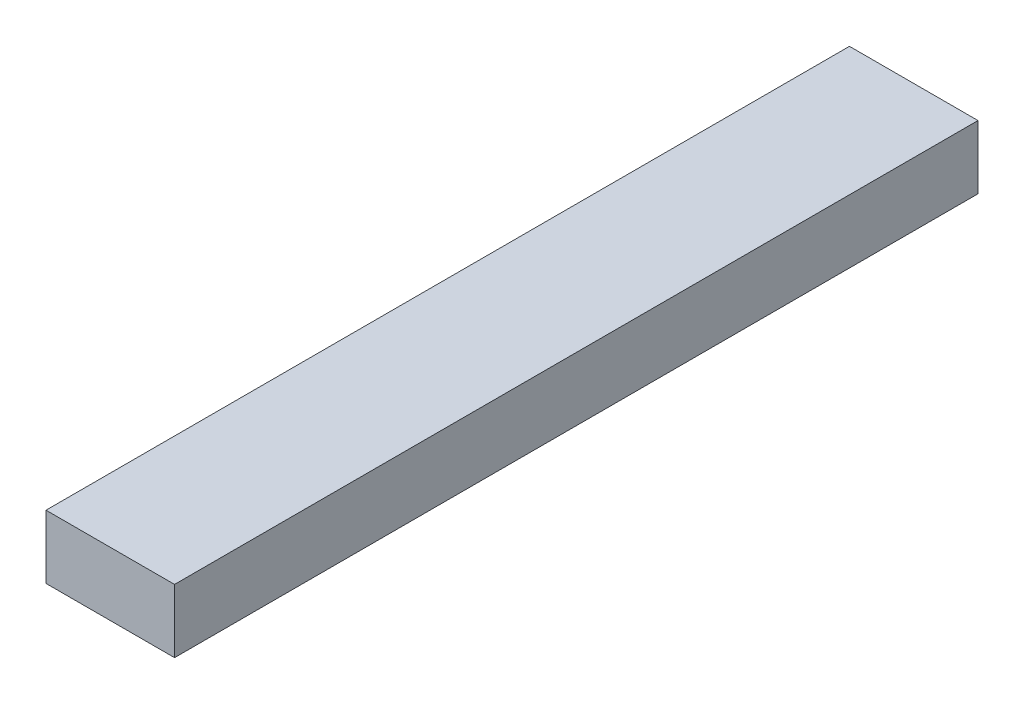
SolidWorks part; units mm, degrees
ref_plane "Front Plane" through (0, 0, 0) normal (0, 0, 1) x (1, 0, 0)
ref_plane "Top Plane" through (0, 0, 0) normal (0, 1, 0) x (1, 0, 0)
ref_plane "Right Plane" through (0, 0, 0) normal (1, 0, 0) x (0, 0, -1)
sketch "Sketch1" plane through (0, 0, 0) normal (0, 0, 1) x (1, 0, 0)
  line L1 (-4.72, -2.33) -> (4.72, -2.33)
  line L2 (-4.72, -2.33) -> (-4.72, 2.33)
  line L3 (-4.72, 2.33) -> (4.72, 2.33)
  line L4 (4.72, -2.33) -> (4.72, 2.33)
  line L5 (-4.72, -2.33) -> (4.72, 2.33) construction
  line L6 (-4.72, 2.33) -> (4.72, -2.33) construction
  point P0 (0, 0)
  dimension "D1" = 9.44
  dimension "D2" = 4.66
extrude "Boss-Extrude1" add sketch "Sketch1" along normal blind 59
